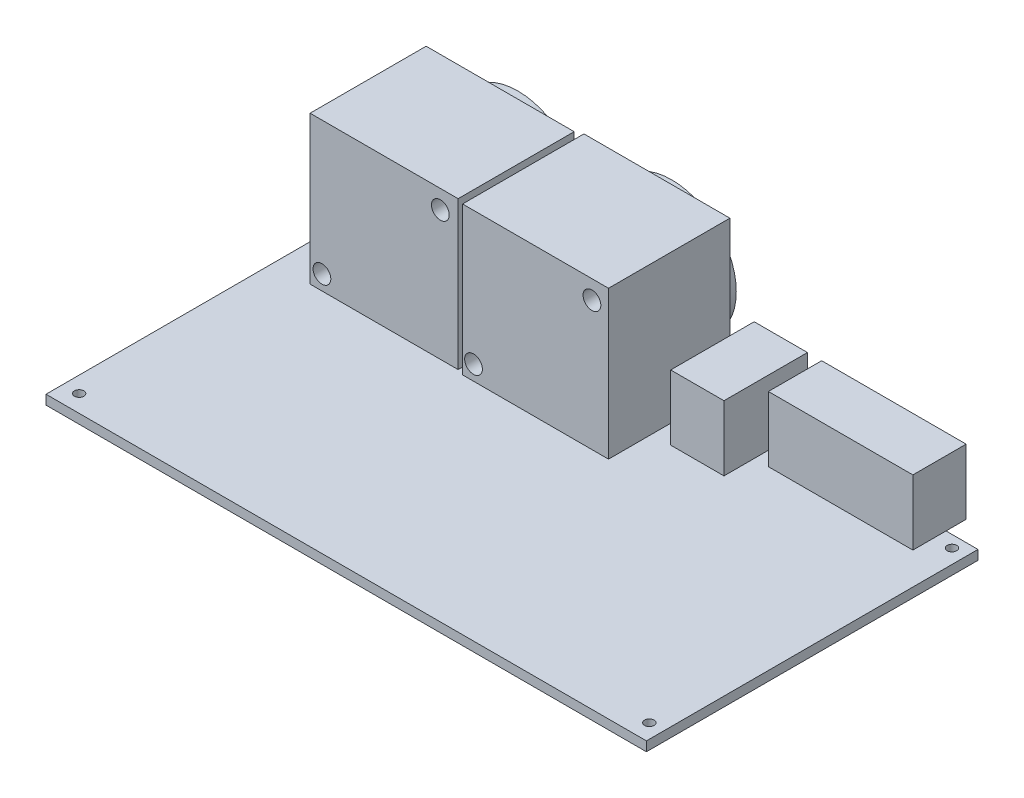
SolidWorks part; units mm, degrees
ref_plane "Front Plane" through (0, 0, 0) normal (0, 0, 1) x (1, 0, 0)
ref_plane "Top Plane" through (0, 0, 0) normal (0, 1, 0) x (1, 0, 0)
ref_plane "Right Plane" through (0, 0, 0) normal (1, 0, 0) x (0, 0, -1)
sketch "Sketch1" plane through (0, 0, 0) normal (0, 1, 0) x (1, 0, 0)
  line L0 (0, 0) -> (101.4, 0)
  line L2 (0, 0) -> (0, 56)
  line L3 (0, 56) -> (101.4, 56)
  line L4 (101.4, 0) -> (101.4, 56)
  circle A0 centre (2.7, 54) radius 0.8
  circle A1 centre (2.7, 2.9) radius 0.8
  circle A2 centre (99, 2.9) radius 0.8
  circle A3 centre (99, 54) radius 0.8
  dimension "D3" = 1.6
  dimension "D1" = 101.4
  dimension "D2" = 56
  dimension "D4" = 2
  dimension "D5" = 2.7
  dimension "D6" = 2.4
  dimension "D7" = 2.9
extrude "Boss-Extrude1" add sketch "Sketch1" along normal blind 1.6
sketch "Sketch2" plane through (0, 1.6, 0) normal (0, 1, 0) x (1, 0, 0)
  line L0 (0, 56) -> (0, 0) construction
  line L1 (6.2, 38.4) -> (31.2, 38.4)
  line L2 (6.2, 38.4) -> (6.2, 58)
  line L3 (6.2, 58) -> (31.2, 58)
  line L4 (31.2, 38.4) -> (31.2, 58)
  line L5 (32.35, 38) -> (57, 38)
  line L6 (32.35, 38) -> (32.35, 58.5)
  line L7 (32.35, 58.5) -> (57, 58.5)
  line L8 (57, 38) -> (57, 58.5)
  line L17 (101.4, 56) -> (0, 56) construction
  dimension "D1" = 6.2
  dimension "D2" = 31.2
  dimension "D3" = 17.6
  dimension "D4" = 2
  dimension "D5" = 32.35
  dimension "D6" = 57
  dimension "D7" = 18
  dimension "D8" = 2.5
extrude "Boss-Extrude2" add sketch "Sketch2" along normal blind 25
sketch "Sketch3" plane through (0, 0, -58.5) normal (0, 0, -1) x (-1, 0, 0)
  line L0 (0, 1.6) -> (0, 0) construction
  line L1 (-101.4, 0) -> (0, 0) construction
  circle A0 centre (-54.2, 23.45) radius 1.5
  circle A1 centre (-34.2, 4.1) radius 1.5
  circle A2 centre (-28.2, 23.45) radius 1.5
  circle A3 centre (-8.2, 4.1) radius 1.5
  dimension "D1" = 3
  dimension "D2" = 8.2
  dimension "D3" = 34.2
  dimension "D4" = 4.1
  dimension "D5" = 23.45
  dimension "D6" = 20
  dimension "D7" = 20
extrude "Cut-Extrude1" cut sketch "Sketch3" against normal through all
sketch "Sketch4" plane through (0, 0, -58) normal (0, 0, -1) x (-1, 0, 0)
  line L0 (-101.4, 0) -> (0, 0) construction
  line L1 (-31.2, 13.9) -> (-18.7, 13.9) construction
  line L3 (-18.7, 13.9) -> (-6.2, 13.9) construction
  line L4 (-6.2, 26.6) -> (-6.2, 1.6) construction
  line L5 (-31.2, 26.6) -> (-31.2, 1.6) construction
  line L6 (-57, 13.9) -> (-44.675, 13.9) construction
  line L7 (-57, 26.6) -> (-57, 1.6) construction
  line L8 (-44.675, 13.9) -> (-32.35, 13.9) construction
  line L9 (-32.35, 26.6) -> (-32.35, 1.6) construction
  circle A0 centre (-18.7, 13.9) radius 10.9
  circle A1 centre (-44.675, 13.9) radius 10.9
  dimension "D1" = 21.8
  dimension "D2" = 13.9
extrude "Boss-Extrude3" add sketch "Sketch4" along normal blind 3
sketch "Sketch5" plane through (0, 1.6, 0) normal (0, 1, 0) x (1, 0, 0)
  line L0 (101.4, 0) -> (101.4, 56) construction
  line L1 (60.2, 59.4) -> (69.2, 59.4)
  line L2 (60.2, 59.4) -> (60.2, 45.3)
  line L3 (60.2, 45.3) -> (69.2, 45.3)
  line L4 (69.2, 59.4) -> (69.2, 45.3)
  line L5 (71.6, 50.4) -> (96, 50.4)
  line L6 (71.6, 50.4) -> (71.6, 59.4)
  line L7 (71.6, 59.4) -> (96, 59.4)
  line L8 (96, 50.4) -> (96, 59.4)
  line L9 (101.4, 56) -> (57, 56) construction
  dimension "D1" = 9
  dimension "D2" = 14.1
  dimension "D3" = 24.4
  dimension "D4" = 9
  dimension "D5" = 5.4
  dimension "D6" = 32.2
  dimension "D7" = 3.4
extrude "Boss-Extrude4" add sketch "Sketch5" along normal blind 11
